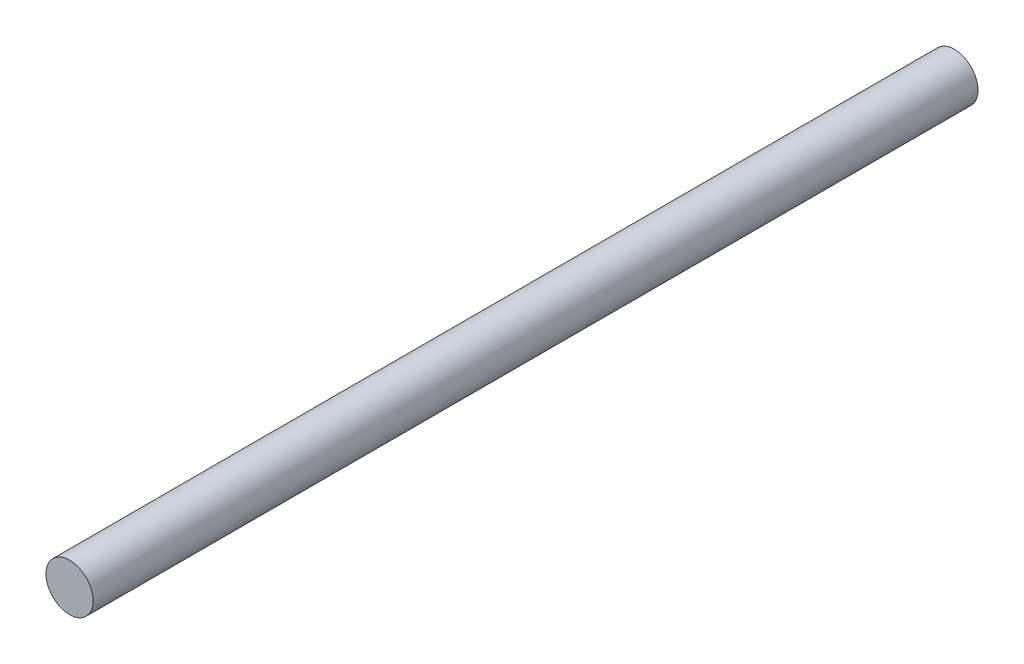
SolidWorks part; units mm, degrees
ref_plane "Front Plane" through (0, 0, 0) normal (0, 0, 1) x (1, 0, 0)
ref_plane "Top Plane" through (0, 0, 0) normal (0, 1, 0) x (1, 0, 0)
ref_plane "Right Plane" through (0, 0, 0) normal (1, 0, 0) x (0, 0, -1)
sketch "Sketch1" plane through (0, 0, 0) normal (0, 0, 1) x (1, 0, 0)
  circle A0 centre (0, 0) radius 8
  dimension "D1" = 16
extrude "Boss-Extrude1" add sketch "Sketch1" along normal blind 300
